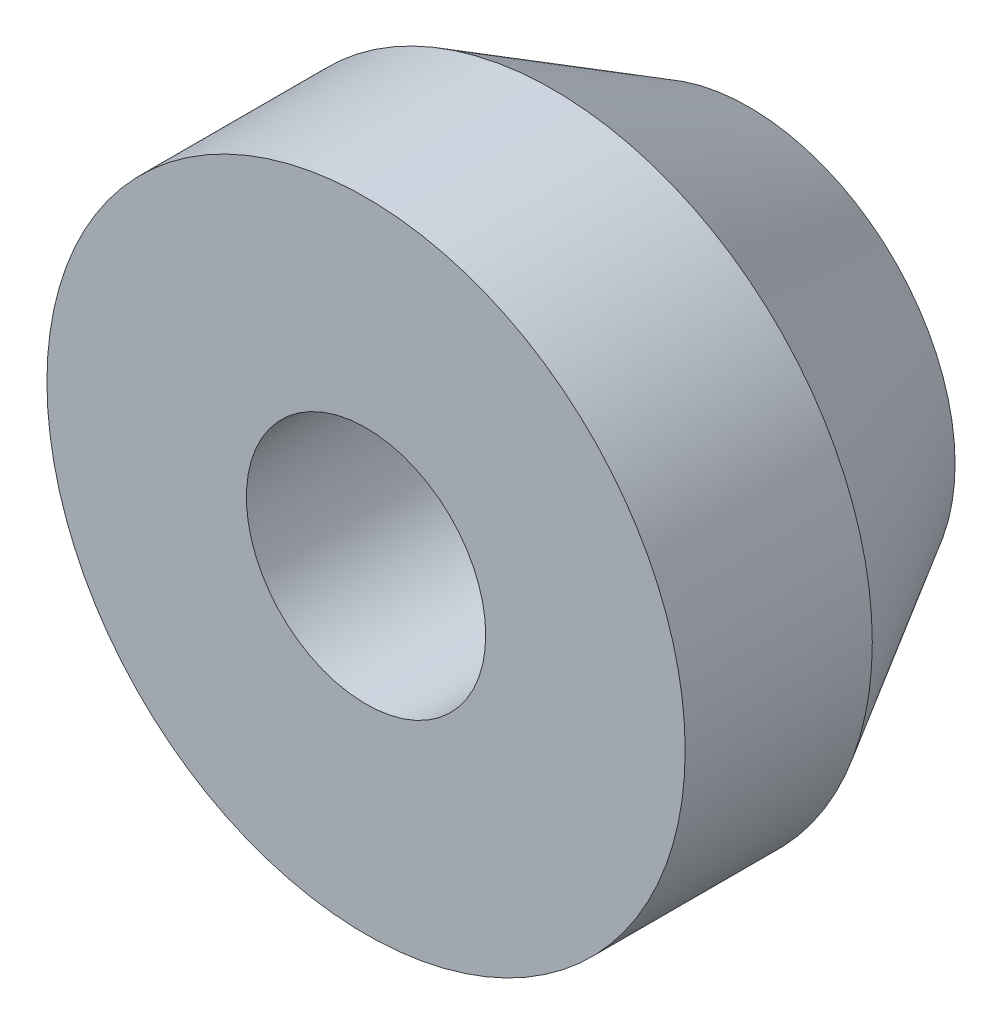
SolidWorks part; units mm, degrees
ref_plane "Front Plane" through (0, 0, 0) normal (0, 0, 1) x (1, 0, 0)
ref_plane "Top Plane" through (0, 0, 0) normal (0, 1, 0) x (1, 0, 0)
ref_plane "Right Plane" through (0, 0, 0) normal (1, 0, 0) x (0, 0, -1)
sketch "Sketch1" plane through (0, 0, 0) normal (0, 1, 0) x (1, 0, 0)
  line L0 (0, 0) -> (0, 21.6884) construction
  line L1 (-12.7, 15.24) -> (-12.7, 0)
  line L2 (-12.7, 15.24) -> (-4.7625, 15.24)
  line L3 (-12.7, 0) -> (-4.7625, 0)
  line L5 (-4.7625, 15.24) -> (-4.7625, 0)
  dimension "D1" = 25.4
  dimension "D2" = 15.24
  dimension "D3" = 9.525
revolve "Revolve1" add sketch "Sketch1" angle 360 about L0
chamfer "Chamfer1" distance 4.5 angle 60 1 edges at (12.7, 0, -15.24)
